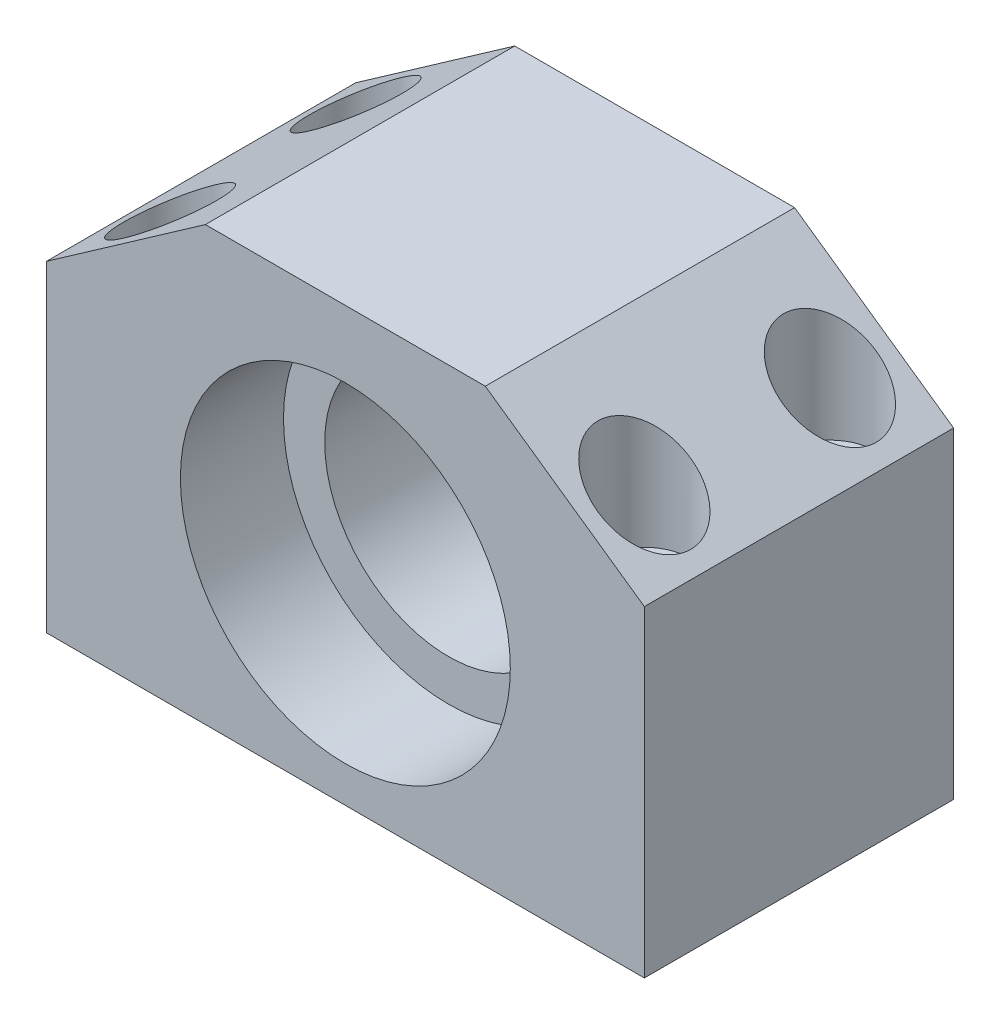
SolidWorks part; units mm, degrees
material "1.0037 (S235JR)"
ref_plane "Płaszczyzna przednia" through (0, 0, 0) normal (0, 0, 1) x (1, 0, 0)
ref_plane "Płaszczyzna górna" through (0, 0, 0) normal (0, 1, 0) x (1, 0, 0)
ref_plane "Płaszczyzna prawa" through (0, 0, 0) normal (1, 0, 0) x (0, 0, -1)
sketch "Szkic1" plane through (0, 0, 0) normal (0, 1, 0) x (1, 0, 0)
  line L1 (-29, -15) -> (29, -15)
  line L2 (-29, -15) -> (-29, 15)
  line L3 (-29, 15) -> (29, 15)
  line L4 (29, -15) -> (29, 15)
  line L5 (-29, -15) -> (29, 15) construction
  line L6 (-29, 15) -> (29, -15) construction
  point P0 (0, 0)
  dimension "D1" = 30
  dimension "D2" = 58
extrude "Dodanie-wyciągnięcie1" add sketch "Szkic1" along normal blind 42
sketch "Szkic3" plane through (0, 0, 15) normal (0, 0, 1) x (1, 0, 0)
  line L0 (0, 42) -> (0, 0) construction
  line L1 (-29, 42) -> (29, 42) construction
  line L2 (-29, 0) -> (29, 0) construction
  circle A0 centre (0, 19.5) radius 12
  dimension "D1" = 24
  dimension "D2" = 19.5
extrude "Wytnij-wyciągnięcie2" cut sketch "Szkic3" against normal through all
sketch "Szkic4" plane through (0, 0, 15) normal (0, 0, 1) x (1, 0, 0)
  circle A0 centre (0, 19.5) radius 16
  dimension "D1" = 32
extrude "Wytnij-wyciągnięcie3" cut sketch "Szkic4" against normal blind 10
mirror "Lustro1" about plane through (0, 0, 0) normal (0, 0, 1) of "Wytnij-wyciągnięcie3"
sketch "Szkic5" plane through (0, 42, 0) normal (0, 1, 0) x (1, 0, 0)
  line L8 (23, -9) -> (23, 9)
  line L9 (23, 9) -> (-23, 9)
  line L10 (-23, 9) -> (-23, -9)
  line L11 (-23, -9) -> (23, -9)
  line L12 (23, -9) -> (23, 9)
  line L13 (23, 9) -> (-23, 9)
  line L14 (-23, 9) -> (-23, -9)
  line L15 (-23, -9) -> (23, -9)
  dimension "D1" = 6
hole_wizard "Pogłębienie walcowe pod M5 Wkręt do części metalowych z łbem sześciokątnym1" positions "Szkic9" profile "Szkic6" counterbore size "M5" standard "Ansi Metric" end condition through all
sketch "Szkic9" plane through (0, 42, 0) normal (0, 1, 0) x (1, 0, 0)
  point P0 (-23, -9)
  point P3 (-23, 9)
  point P6 (23, -9)
  point P9 (23, 9)
sketch "Szkic6" plane through (-23, 42, 9) normal (1, 0, 0) x (0, 0, 1)
  line L0 (0, 0) -> (0, 42)
  line L1 (0, 42) -> (2.75, 42)
  line L3 (2.75, 42) -> (2.75, 15)
  line L4 (2.75, 15) -> (4.5, 15)
  line L5 (4.5, 15) -> (4.5, 0)
  line L7 (4.5, 0) -> (0, 0)
  line L11 (0, -6.35) -> (0, 107.95) construction
  dimension "Średnica otworu na wylot" = 5.5
  dimension "Głębokość otworu na wylot" = 42
  dimension "Średnica pogłębienia walcowego" = 9
  dimension "Głębokość pogłębienia walcowego" = 15
sketch "Szkic10" plane through (0, 0, -15) normal (0, 0, -1) x (-1, 0, 0)
  line L0 (25, 34) -> (13.5748, 42) construction
  line L1 (-13.5748, 42) -> (-25, 34) construction
  line L2 (32.5, 28.7484) -> (13.5748, 42)
  line L3 (-13.5748, 42) -> (-32.5, 28.7484)
  line M2 (29, 0) -> (29, 42)
  line M3 (29, 42) -> (-29, 42)
  line M4 (-29, 42) -> (-29, 0)
  dimension "D1" = 65
extrude "Wytnij-wyciągnięcie4" cut sketch "Szkic10" against normal through all contours L3 M3 M4 | L2 M2 M3
